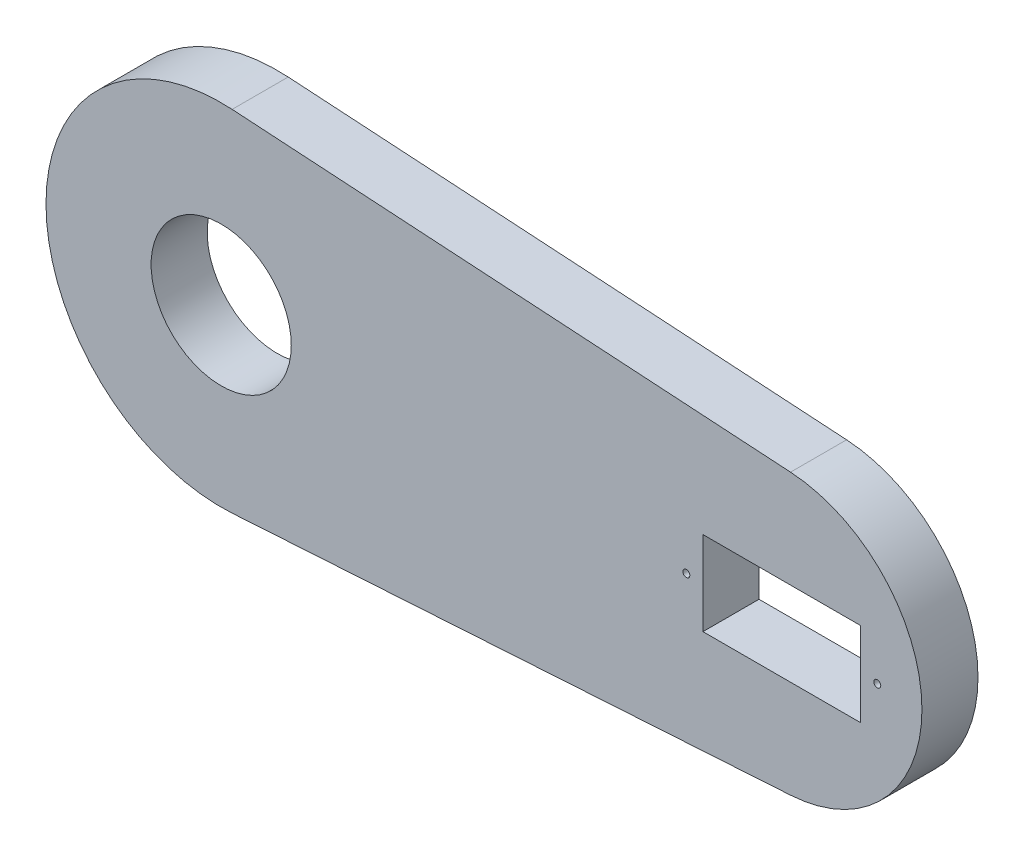
SolidWorks part; units mm, degrees
material "Haya"
ref_plane "Alzado" through (0, 0, 0) normal (0, 0, 1) x (1, 0, 0)
ref_plane "Planta" through (0, 0, 0) normal (0, 1, 0) x (1, 0, 0)
ref_plane "Vista lateral" through (0, 0, 0) normal (1, 0, 0) x (0, 0, -1)
sketch "Croquis1" plane through (0, 0, 0) normal (0, 0, 1) x (1, 0, 0)
  line L0 (1.5625, 24.9511) -> (81.25, 19.9609)
  line L1 (91.25, -6) -> (68.75, -6)
  line L2 (81.25, -19.9609) -> (1.5625, -24.9511)
  line L3 (91.25, -6) -> (91.25, 6)
  line L4 (68.75, -6) -> (68.75, 6)
  line L5 (91.25, 6) -> (68.75, 6)
  line L6 (91.25, -6) -> (68.75, 6) construction
  line L7 (68.75, -6) -> (91.25, 6) construction
  arc A0 (1.5625, 24.9511) -> (1.5625, -24.9511) centre (0, 0) ccw
  arc A1 (81.25, -19.9609) -> (81.25, 19.9609) centre (80, 0) ccw
  circle A2 centre (0, 0) radius 0.8
  circle A3 centre (80, 0) radius 11 construction
  circle A4 centre (66.375, 0) radius 0.5
  circle A5 centre (93.625, 0) radius 0.5
  circle A6 centre (7.5, 0) radius 0.8
  circle A7 centre (0, -7.5) radius 0.8
  circle A8 centre (-7.5, 0) radius 0.8
  circle A9 centre (0, 7.5) radius 0.8
  point P17 (91.25, 0)
  point P18 (68.75, 0)
  point P30 (0, 0)
  dimension "D1" = 25
  dimension "D2" = 20
  dimension "D4" = 1.6
  dimension "D5" = 22
  dimension "D8" = 1
  dimension "D9" = 1
  dimension "D14" = 1.6
  dimension "D15" = 4
  dimension "D3" = 80
  dimension "D6" = 12
  dimension "D7" = 22.5
  dimension "D10" = 2.375
  dimension "D11" = 2.375
  dimension "D12" = 27.25
  dimension "D13" = 13.625
  dimension "D16" = 7.5
extrude "Saliente-Extruir1" add sketch "Croquis1" against normal blind 8
sketch "Croquis2" plane through (0, 0, 0) normal (0, 0, 1) x (1, 0, 0)
  circle A0 centre (0, 0) radius 10
  dimension "D1" = 20
extrude "Cortar-Extruir1" cut sketch "Croquis2" against normal through all
